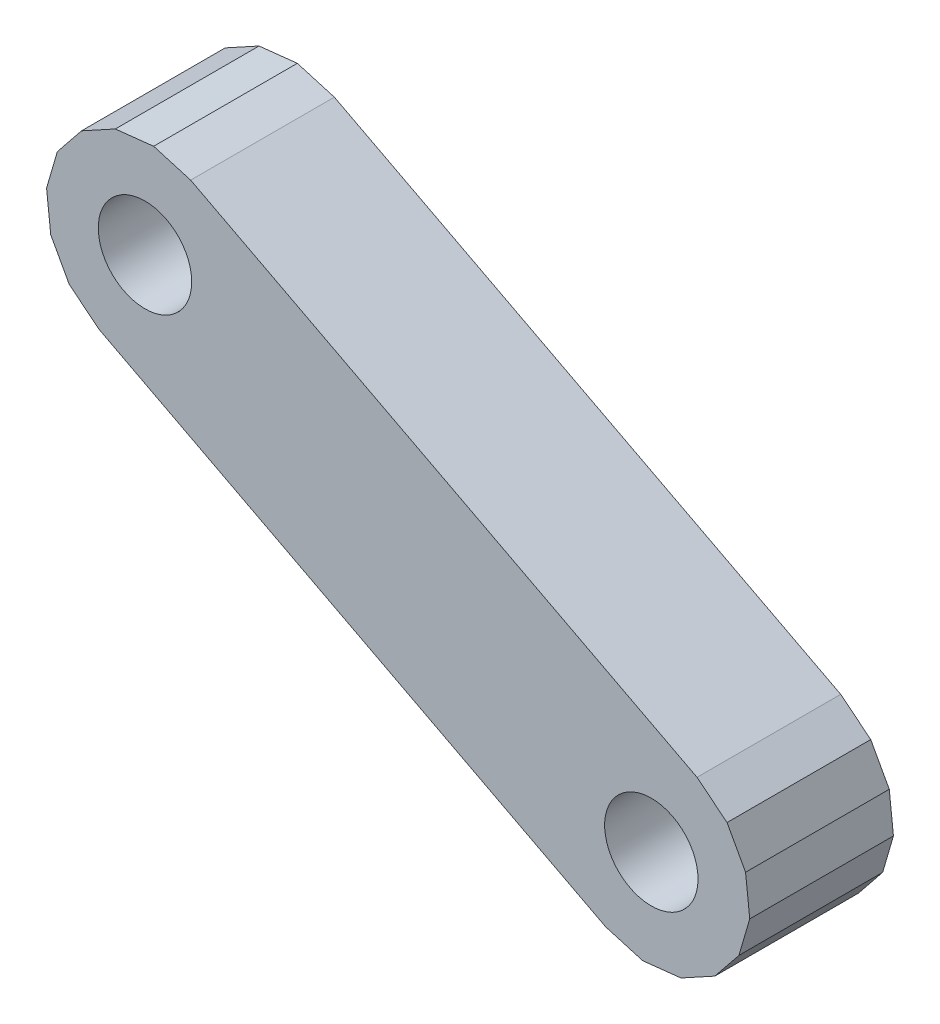
SolidWorks part; units mm, degrees
ref_plane "前视基准面" through (0, 0, 0) normal (0, 0, 1) x (1, 0, 0)
ref_plane "上视基准面" through (0, 0, 0) normal (0, 1, 0) x (1, 0, 0)
ref_plane "右视基准面" through (0, 0, 0) normal (1, 0, 0) x (0, 0, -1)
other "Configuration Table"
sketch "草图1" plane through (0, 0, 0) normal (0, 0, 1) x (1, 0, 0)
  line L0 (-43.7332, 35.82) -> (-45.406, 37.1642)
  line L1 (-45.406, 37.1642) -> (-46.4371, 39.0463)
  line L2 (-46.4371, 39.0463) -> (-46.6694, 41.1797)
  line L3 (-46.6694, 41.1797) -> (-46.0676, 43.2396)
  line L4 (-46.0676, 43.2396) -> (-44.7234, 44.9124)
  line L5 (-44.7234, 44.9124) -> (-42.8413, 45.9434)
  line L6 (-42.8413, 45.9434) -> (-40.7079, 46.1757)
  line L7 (-40.7079, 46.1757) -> (-38.648, 45.574)
  line L8 (-38.648, 45.574) -> (-10.4574, 30.877)
  line L9 (-10.4574, 30.877) -> (-8.7846, 29.5328)
  line L10 (-8.7846, 29.5328) -> (-7.7535, 27.6507)
  line L11 (-7.7535, 27.6507) -> (-7.5212, 25.5173)
  line L12 (-7.5212, 25.5173) -> (-8.123, 23.4574)
  line L13 (-8.123, 23.4574) -> (-9.4672, 21.7846)
  line L14 (-9.4672, 21.7846) -> (-11.3493, 20.7535)
  line L15 (-11.3493, 20.7535) -> (-13.4827, 20.5212)
  line L16 (-13.4827, 20.5212) -> (-15.5426, 21.123)
  line L17 (-15.5426, 21.123) -> (-43.7332, 35.82)
  dimension "x0" = 43.7332
  dimension "x1" = 45.406
  dimension "x2" = 46.4371
  dimension "x3" = 46.6694
  dimension "x4" = 46.0676
  dimension "x5" = 44.7234
  dimension "x6" = 42.8413
  dimension "x7" = 40.7079
  dimension "x8" = 38.648
  dimension "x9" = 10.4574
  dimension "x10" = 8.7846
  dimension "x11" = 7.7535
  dimension "x12" = 7.5212
  dimension "x13" = 8.123
  dimension "x14" = 9.4672
  dimension "x15" = 11.3493
  dimension "x16" = 13.4827
  dimension "x17" = 15.5426
  dimension "y0" = 35.82
  dimension "y1" = 37.1642
  dimension "y2" = 39.0463
  dimension "y3" = 41.1797
  dimension "y4" = 43.2396
  dimension "y5" = 44.9124
  dimension "y6" = 45.9434
  dimension "y7" = 46.1757
  dimension "y8" = 45.574
  dimension "y9" = 30.877
  dimension "y10" = 29.5328
  dimension "y11" = 27.6507
  dimension "y12" = 25.5173
  dimension "y13" = 23.4574
  dimension "y14" = 21.7846
  dimension "y15" = 20.7535
  dimension "y16" = 20.5212
  dimension "y17" = 21.123
extrude "High_slider_link" add sketch "草图1" along normal blind 8
sketch "草图2" plane through (0, 0, 8) normal (0, 0, 1) x (1, 0, 0)
  circle A0 centre (-41.1906, 40.697) radius 2.6
  dimension "diameter" = 5.2
  dimension "x" = 41.1906
  dimension "y" = 40.697
extrude "Pin_bore" cut sketch "草图2" against normal through all
sketch "草图3" plane through (0, 0, 8) normal (0, 0, 1) x (1, 0, 0)
  circle A0 centre (-13, 26) radius 2.6
  dimension "diameter" = 5.2
  dimension "x" = 13
  dimension "y" = 26
extrude "切除-拉伸2" cut sketch "草图3" against normal through all
